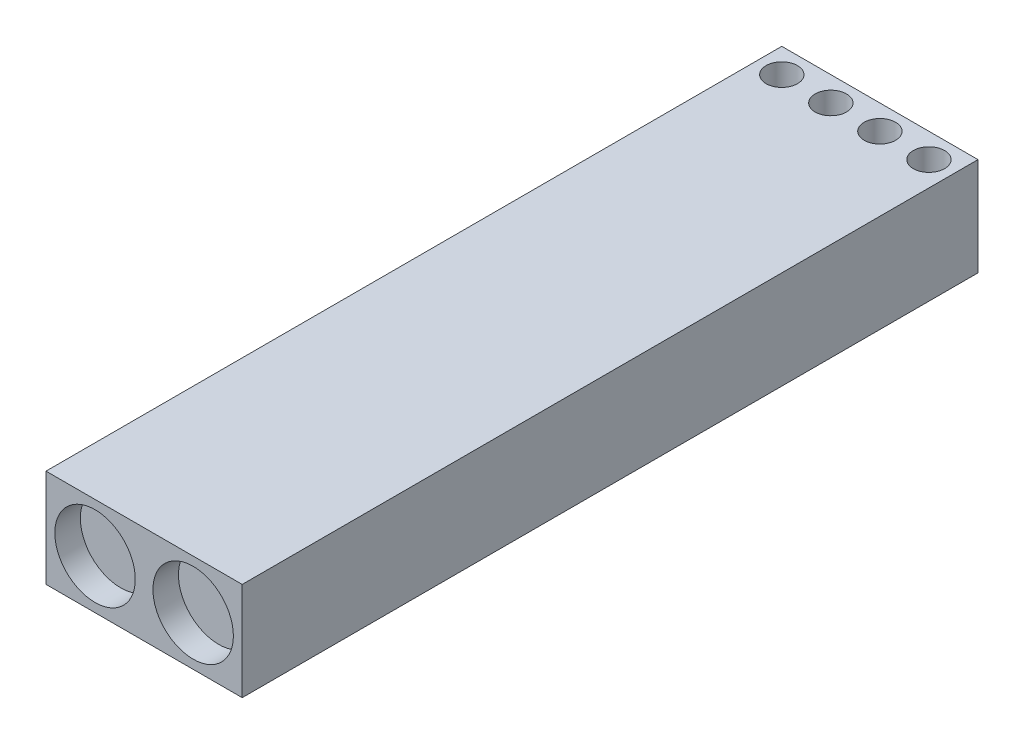
SolidWorks part; units mm, degrees
ref_plane "正面" through (0, 0, 0) normal (0, 0, 1) x (1, 0, 0)
ref_plane "平面" through (0, 0, 0) normal (0, 1, 0) x (1, 0, 0)
ref_plane "右側面" through (0, 0, 0) normal (1, 0, 0) x (0, 0, -1)
sketch "ｽｹｯﾁ1" plane through (0, 0, 0) normal (0, 0, 1) x (1, 0, 0)
  line L1 (-10, 10) -> (10, 10)
  line L2 (-10, 10) -> (-10, -10)
  line L3 (-10, -10) -> (10, -10)
  line L4 (10, 10) -> (10, -10)
  line L5 (-10, 10) -> (10, -10) construction
  line L6 (-10, -10) -> (10, 10) construction
  point P0 (0, 0)
  dimension "D1" = 20
  dimension "D2" = 20
extrude "ﾎﾞｽ - 押し出し1" add sketch "ｽｹｯﾁ1" along normal blind 150
sketch "ｽｹｯﾁ2" plane through (0, 0, 150) normal (0, 0, 1) x (1, 0, 0)
  circle A0 centre (0, 0) radius 8.2
  dimension "D1" = 16.4
extrude "ｶｯﾄ - 押し出し1" cut sketch "ｽｹｯﾁ2" against normal blind 5.2
sketch "ｽｹｯﾁ3" plane through (0, 10, 0) normal (0, 1, 0) x (1, 0, 0)
  line L0 (10, 0) -> (-10, 0) construction
  line L1 (10, -150) -> (10, 0) construction
  circle A0 centre (5, -5) radius 3.2
  dimension "D1" = 6.4
  dimension "D2" = 5
  dimension "D3" = 5
extrude "ｶｯﾄ - 押し出し2" cut sketch "ｽｹｯﾁ3" against normal blind 18
mirror "ﾐﾗｰ1" about plane through (0, 0, 0) normal (1, 0, 0) of "ｶｯﾄ - 押し出し2"
mirror "ﾐﾗｰ2" about plane through (-10, 10, 150) normal (1, 0, 0) of "ﾐﾗｰ1", "ｶｯﾄ - 押し出し1", "ﾎﾞｽ - 押し出し1", "ｶｯﾄ - 押し出し2"
